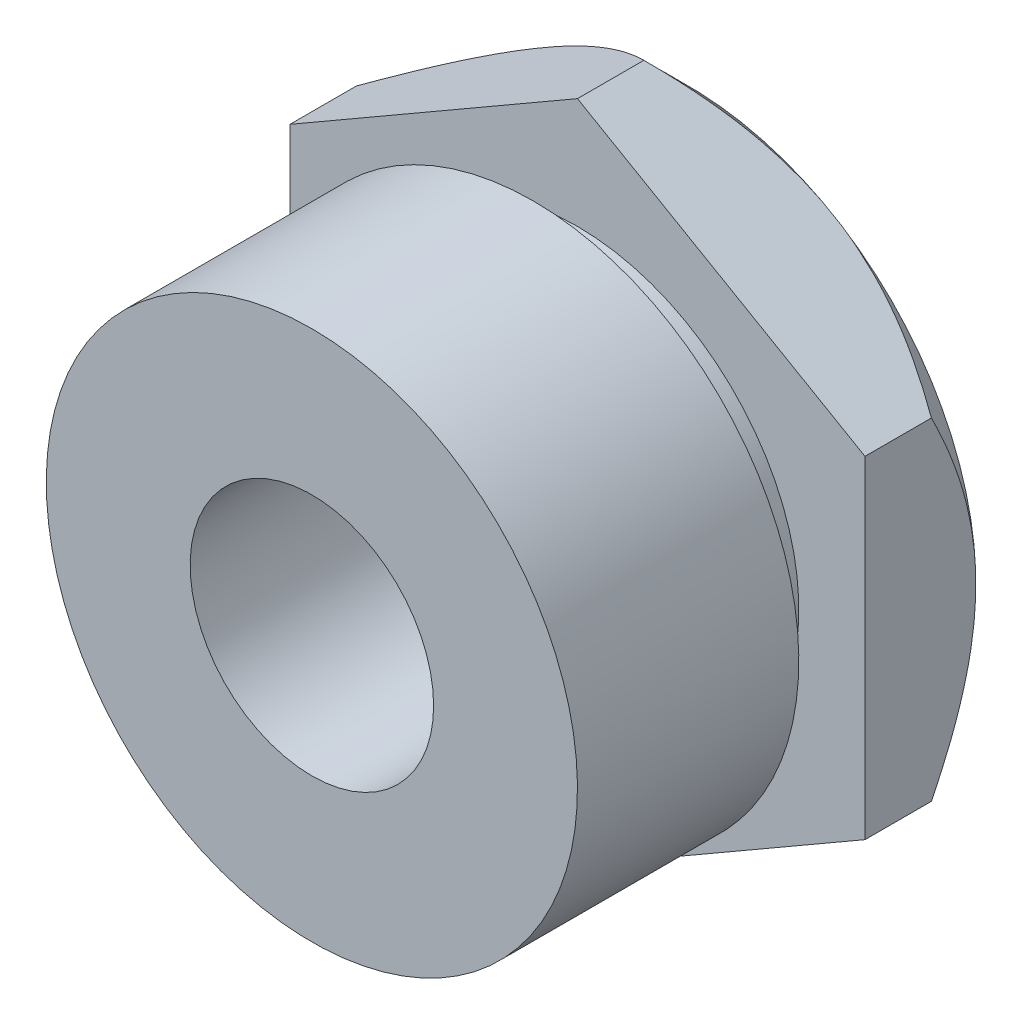
SolidWorks part; units mm, degrees
ref_plane "前视基准面" through (0, 0, 0) normal (0, 0, 1) x (1, 0, 0)
ref_plane "上视基准面" through (0, 0, 0) normal (0, 1, 0) x (1, 0, 0)
ref_plane "右视基准面" through (0, 0, 0) normal (1, 0, 0) x (0, 0, -1)
sketch "草图1" plane through (0, 0, 0) normal (1, 0, 0) x (0, 0, -1)
  line L0 (0, 0) -> (-17, 0) construction
  line L1 (-17, 0) -> (-17, 12)
  line L2 (-17, 12) -> (-7, 12)
  line L3 (-7, 12) -> (-7, 10)
  line L4 (-7, 10) -> (-5, 10)
  line L5 (-5, 10) -> (-5, 15)
  line L6 (-5, 15) -> (0, 15)
  line L7 (-17, 0) -> (0, 0)
  line L8 (0, 15) -> (0, 0)
  point P0 (1.8991, 15.0591)
  dimension "D1" = 2
  dimension "D2" = 24
  dimension "D3" = 17
  dimension "D4" = 5
  dimension "D5" = 10
  dimension "D6" = 30
revolve "旋转1" add sketch "草图1" angle 360 about L0
cosmetic thread "装饰螺纹线1" parameters "D2"=23
chamfer "倒角1" distance 2 angle 45 1 edges at (0, 15, 0)
sketch "草图2" plane through (0, 0, 17) normal (0, 0, 1) x (1, 0, 0)
  circle A0 centre (0, 0) radius 5.5
  dimension "D1" = 11
extrude "切除-拉伸1" cut sketch "草图2" against normal through all both and the other way through all
sketch "草图3" plane through (0, 0, 5) normal (0, 0, 1) x (1, 0, 0)
  line L0 (0, 0) -> (0, 15) construction
  line L1 (0, 15) -> (-12.9904, 7.5)
  line L2 (-12.9904, 7.5) -> (-12.9904, -7.5)
  line L3 (-12.9904, -7.5) -> (0, -15)
  line L4 (0, -15) -> (12.9904, -7.5)
  line L5 (12.9904, -7.5) -> (12.9904, 7.5)
  line L6 (12.9904, 7.5) -> (0, 15)
  circle A0 centre (0, 0) radius 15 construction
  circle A1 centre (0, 0) radius 15 construction
  point P1 (0, 0)
  point P10 (11.6382, 6.7193)
extrude "切除-拉伸2" cut sketch "草图3" against normal through all both and the other way through all flip side to cut
